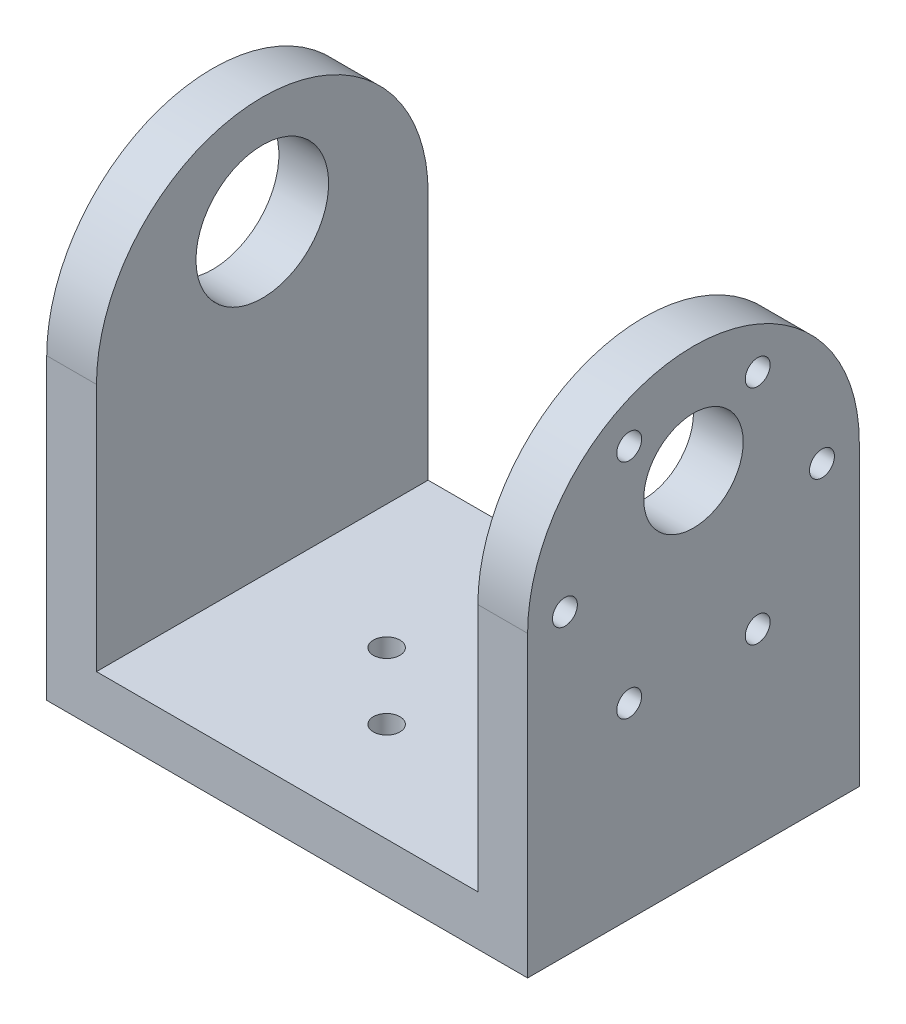
SolidWorks part; units mm, degrees
ref_plane "Front Plane" through (0, 0, 0) normal (0, 0, 1) x (1, 0, 0)
ref_plane "Top Plane" through (0, 0, 0) normal (0, 1, 0) x (1, 0, 0)
ref_plane "Right Plane" through (0, 0, 0) normal (1, 0, 0) x (0, 0, -1)
sketch "Sketch2" plane through (0, 0, 0) normal (0, 1, 0) x (1, 0, 0)
  line L1 (-21.5, 31.1985) -> (28.5, 31.1985)
  line L2 (-21.5, 31.1985) -> (-21.5, -8.8015)
  line L3 (-21.5, -8.8015) -> (28.5, -8.8015)
  line L4 (28.5, 31.1985) -> (28.5, -8.8015)
  point P0 (0, 0)
  dimension "D1" = 50
  dimension "D2" = 40
extrude "Boss-Extrude2" add sketch "Sketch2" along normal blind 2 and the other way blind 4
sketch "Sketch4" plane through (-21.5, 0, 0) normal (-1, 0, 0) x (0, 0, 1)
  line L1 (8.8015, 2) -> (-31.1985, 2)
  line L2 (8.8015, 2) -> (8.8015, 32)
  line L4 (-31.1985, 2) -> (-31.1985, 32)
  arc A0 (8.8015, 32) -> (-31.1985, 32) centre (-11.1985, 32) ccw
  point P5 (-11.1985, 52)
  dimension "D1" = 20
  dimension "D2" = 50
extrude "Boss-Extrude3" add sketch "Sketch4" against normal blind 2 and the other way blind 4
sketch "Sketch5" plane through (28.5, 0, 0) normal (1, 0, 0) x (0, 0, -1)
  line L1 (-8.8015, -4) -> (31.1985, -4)
  line L2 (-8.8015, -4) -> (-8.8015, 32)
  line L4 (31.1985, -4) -> (31.1985, 32)
  arc A0 (31.1985, 32) -> (-8.8015, 32) centre (11.1985, 32) ccw
extrude "Boss-Extrude4" add sketch "Sketch5" against normal blind 2 and the other way blind 4
sketch "Sketch7" plane through (-21.5, 0, 0) normal (-1, 0, 0) x (0, 0, 1)
  line L0 (19.236, 32) -> (-43.1388, 32) construction
  circle A0 centre (-11.1985, 32) radius 15.5 construction
  circle A1 centre (4.3015, 32) radius 1.5
  circle A2 centre (-3.4485, 18.5766) radius 1.5
  circle A3 centre (-18.9485, 18.5766) radius 1.5
  circle A4 centre (-26.6985, 32) radius 1.5
  circle A5 centre (-18.9485, 45.4234) radius 1.5
  circle A6 centre (-3.4485, 45.4234) radius 1.5
  circle A7 centre (-11.1985, 39) radius 6
  point P18 (-11.1985, 32)
  dimension "D1" = 31
  dimension "D2" = 3
  dimension "D7" = 12
  dimension "D4" = 13.4234
  dimension "D5" = 7.75
  dimension "D6" = 7
  dimension "D3" = 6
extrude "Cut-Extrude1" cut sketch "Sketch7" against normal blind 92 and the other way blind 10
sketch "Sketch8" plane through (0, 2, 0) normal (0, 1, 0) x (1, 0, 0)
  line L1 (26.5, -8.8015) -> (26.5, 31.1985) construction
  line L2 (-19.5, -8.8015) -> (26.5, -8.8015) construction
  circle A0 centre (3.5, 11.1985) radius 3
  point P14 (26.5, 11.1985)
  point P15 (3.5, -8.8015)
  dimension "D6" = 6
extrude "Cut-Extrude2" cut sketch "Sketch8" against normal blind 92
sketch "Çizim4" plane through (0, 2, 0) normal (0, 1, 0) x (1, 0, 0)
  line L0 (6.5, 11.2623) -> (6, 11.2623)
  line L1 (6, 11.2623) -> (6, 12.8581)
  line L2 (6, 12.8581) -> (6, 9.539)
  circle A0 centre (3.5, 11.1985) radius 3.0007
  point P13 (3.5, 11.1985)
  circle M10 centre (3.5, 11.1985) radius 3
  dimension "D2" = 6.0014
  dimension "D1" = 0.5
  dimension "D3" = 1.5958
  dimension "D4" = 3.3191
extrude "Yükseklik-Ekstrüzyon2" add sketch "Çizim4" against normal blind 6 contours L0 L2 M10 | L1 L0 M10
sketch "Sketch9" plane through (0, 0, -31.1985) normal (0, 0, -1) x (-1, 0, 0)
  line L1 (21.5, 2) -> (32.5, 2)
  line L2 (21.5, 2) -> (21.5, -4)
  line L3 (21.5, -4) -> (32.5, -4)
  line L4 (32.5, 2) -> (32.5, -4)
extrude "Boss-Extrude5" add sketch "Sketch9" against normal up to vertex (40 mm away)
sketch "Sketch10" plane through (0, 2, 0) normal (0, 1, 0) x (1, 0, 0)
  line L1 (-32.5, 31.1985) -> (-25.5, 31.1985)
  line L2 (-32.5, 31.1985) -> (-32.5, -8.8015)
  line L3 (-32.5, -8.8015) -> (-25.5, -8.8015)
  line L4 (-25.5, 31.1985) -> (-25.5, -8.8015)
extrude "Cut-Extrude3" cut sketch "Sketch10" against normal blind 10
sketch "Çizim8" plane through (-19.5, 0, 0) normal (1, 0, 0) x (0, 0, -1)
  circle A0 centre (-4.3015, 32) radius 2.3957
  circle A2 centre (3.4485, 45.4234) radius 2.3957
  circle A3 centre (18.9485, 45.4234) radius 2.3957
  circle A4 centre (26.6985, 32) radius 2.3957
  circle A5 centre (18.9485, 18.5766) radius 2.3957
  circle A6 centre (3.4485, 18.5766) radius 2.3957
  point P21 (11.1985, 32)
  dimension "D1" = 6
extrude "Kes-Ekstrüzyon2" cut sketch "Çizim8" along normal blind 48
sketch "Çizim9" plane through (-25.5, 0, 0) normal (-1, 0, 0) x (0, 0, 1)
  line L3 (8.8015, -4) -> (8.8015, 32)
  line L4 (-31.1985, 32) -> (-31.1985, -4)
  line L5 (-31.1985, -4) -> (8.8015, -4)
  line L6 (8.8015, -4) -> (8.8015, 32)
  line L7 (-31.1985, 32) -> (-31.1985, -4)
  line L8 (-31.1985, -4) -> (8.8015, -4)
  arc A1 (8.8015, 32) -> (-31.1985, 32) centre (-11.1985, 32) ccw
  arc A2 (8.8015, 32) -> (-31.1985, 32) centre (-11.1985, 32) ccw
  dimension "D1" = 0
extrude "Yükseklik-Ekstrüzyon3" add sketch "Çizim9" against normal blind 6
sketch "Çizim10" plane through (-25.5, 0, 0) normal (-1, 0, 0) x (0, 0, 1)
  circle A1 centre (-11.1985, 39) radius 8
  dimension "D2" = 16
extrude "Kes-Ekstrüzyon3" cut sketch "Çizim10" against normal blind 6
sketch "Çizim11" plane through (0, -4, 0) normal (0, -1, 0) x (1, 0, 0)
  line L0 (3.5, -11.1985) -> (11.5, -11.1985)
  circle A1 centre (11.5, -11.1985) radius 1.6
  circle A2 centre (3.5, -19.1985) radius 1.6
  circle A3 centre (-4.5, -11.1985) radius 1.6
  circle A4 centre (3.5, -3.1985) radius 1.6
  point P13 (3.5, -11.1985)
  dimension "D2" = 3.2
  dimension "D1" = 8
  dimension "D3" = 4
extrude "Kes-Ekstrüzyon5" cut sketch "Çizim11" against normal blind 10
sketch "Çizim13" plane through (0, -4, 0) normal (0, -1, 0) x (1, 0, 0)
  circle A0 centre (3.5, -11.1985) radius 3.8842
extrude "Yükseklik-Ekstrüzyon4" add sketch "Çizim13" against normal blind 6
